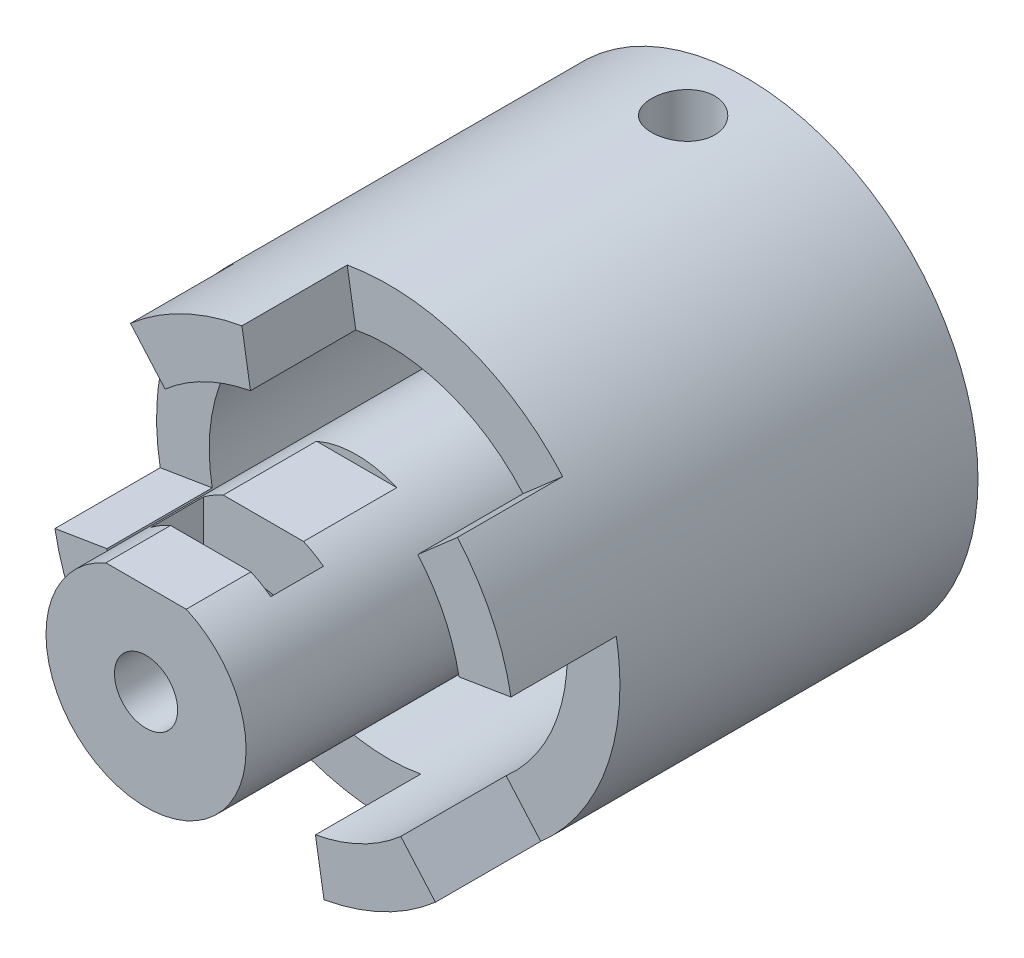
SolidWorks part; units mm, degrees
ref_plane "Front Plane" through (0, 0, 0) normal (0, 0, 1) x (1, 0, 0)
ref_plane "Top Plane" through (0, 0, 0) normal (0, 1, 0) x (1, 0, 0)
ref_plane "Right Plane" through (0, 0, 0) normal (1, 0, 0) x (0, 0, -1)
sketch "Sketch3" plane through (0, 0, 0) normal (1, 0, 0) x (0, 0, -1)
  line L0 (-7.3374, 0) -> (14.1626, 0)
  line L1 (14.1626, 0) -> (14.1626, -3.75)
  line L4 (19.1626, 4.75) -> (-7.3374, 4.75)
  line L5 (-7.3374, 4.75) -> (-7.3374, 0)
  line L6 (-26.8946, 4.75) -> (41.8764, 4.75) construction
  line L7 (14.1626, -3.75) -> (4.1626, -3.75)
  line L8 (4.1626, -3.75) -> (4.1626, -6.25)
  line L9 (4.1626, -6.25) -> (16.1626, -6.25)
  line L16 (21.1626, -3.0474) -> (21.1626, 4.75)
  line L17 (21.1626, 4.75) -> (19.1626, 4.75)
  line L18 (16.1626, -6.25) -> (21.1626, -6.25)
  line L19 (21.1626, -6.25) -> (21.1626, -3.0474)
  dimension "D1" = 21.5
  dimension "D2" = 2.5
  dimension "D3" = 4.75
  dimension "D5" = 5
  dimension "D7" = 10
revolve "Revolve1" add sketch "Sketch3" angle 360 about L6
sketch "Sketch4" plane through (0, 0, -4.1626) normal (0, 0, 1) x (1, 0, 0)
  line L0 (0, 4.75) -> (0, 18.75) construction
  line L2 (0, 4.75) -> (-9.8995, 14.6495) construction
  line L6 (-1.9481, 15.5761) -> (-1.543, 13.1088)
  line L7 (-7.2394, 13.0319) -> (-5.5941, 11.1497)
  circle A0 centre (0, 4.75) radius 11 construction
  arc A1 (-1.9481, 15.5761) -> (-7.2394, 13.0319) centre (0, 4.75) ccw
  circle A2 centre (0, 4.75) radius 8.5 construction
  arc A3 (-1.543, 13.1088) -> (-5.5941, 11.1497) centre (0, 4.75) ccw
  dimension "D1" = 4.5
  dimension "D2" = 45
extrude "Boss-Extrude2" add sketch "Sketch4" along normal blind 5
pattern_circular "CirPattern1" count 4 over 360 about axis through (0, 4.75, 0) along (0, 0, 1) of "Boss-Extrude2"
sketch "Sketch5" plane through (0, 0, 7.3374) normal (0, 0, 1) x (1, 0, 0)
  circle A0 centre (0, 4.75) radius 1.5
  circle A1 centre (0, 4.75) radius 4.75
  arc A2 (-2.0215, 9.0484) -> (2.0215, 9.0484) centre (0, 4.75) ccw construction
  dimension "D2" = 3
  dimension "D1" = 0
extrude "Cut-Extrude1" cut sketch "Sketch5" against normal blind 10
sketch "Sketch7" plane through (0, 0, -21.1626) normal (0, 0, -1) x (-1, 0, 0)
  line L0 (-1.445, 6.2738) -> (1.445, 6.2738)
  arc A0 (-1.445, 6.2738) -> (1.445, 6.2738) centre (0, 4.75) ccw
  circle A1 centre (0, 4.75) radius 11
  circle A4 centre (0, 4.75) radius 11 construction
  dimension "D2" = 4.2
  dimension "D3" = 2.89
  dimension "D1" = 0
extrude "Cut-Extrude2" cut sketch "Sketch7" against normal blind 10
sketch "Sketch8" plane through (0, 0, -21.1626) normal (0, 0, -1) x (-1, 0, 0)
  line L0 (0, 4.75) -> (0, 9.3583) construction
  line L1 (-2.825, 7.2738) -> (2.825, 7.2738)
  line L2 (-2.825, 7.2738) -> (-2.825, 9.7738)
  line L3 (-2.825, 9.7738) -> (2.825, 9.7738)
  line L4 (2.825, 7.2738) -> (2.825, 9.7738)
  line L5 (1.445, 6.2738) -> (-1.445, 6.2738) construction
  dimension "D1" = 5.65
  dimension "D2" = 2.5
  dimension "D3" = 2.825
  dimension "D4" = 1
extrude "Cut-Extrude3" cut sketch "Sketch8" against normal blind 6.5
sketch "Sketch10" plane through (0, 6.2738, 0) normal (0, -1, 0) x (1, 0, 0)
  line L0 (-11, -21.1626) -> (11, -21.1626) construction
  circle A0 centre (0, -18.1626) radius 1.5
  dimension "D1" = 3
  dimension "D2" = 3
extrude "Cut-Extrude5" cut sketch "Sketch10" against normal blind 10
sketch "Sketch12" plane through (0, 0, 7.3374) normal (0, 0, 1) x (1, 0, 0)
  line L0 (-1.9075, 9.1002) -> (1.9075, 9.1002)
  circle A0 centre (0, 4.75) radius 4.75 construction
  arc A1 (1.9075, 9.1002) -> (-1.9075, 9.1002) centre (0, 4.75) ccw
extrude "Cut-Extrude6" cut sketch "Sketch12" against normal blind 10
sketch "Sketch13" plane through (0, 9.1002, 0) normal (0, 1, 0) x (1, 0, 0)
  line L0 (0, 0) -> (0, -5.5754) construction
  line L1 (-2.85, -4.2654) -> (2.85, -4.2654)
  line L2 (-2.85, -4.2654) -> (-2.85, -1.7654)
  line L3 (-2.85, -1.7654) -> (2.85, -1.7654)
  line L4 (2.85, -4.2654) -> (2.85, -1.7654)
  dimension "D1" = 5.7
  dimension "D2" = 2.85
  dimension "D3" = 2.5
extrude "Cut-Extrude7" cut sketch "Sketch13" against normal blind 7.5
